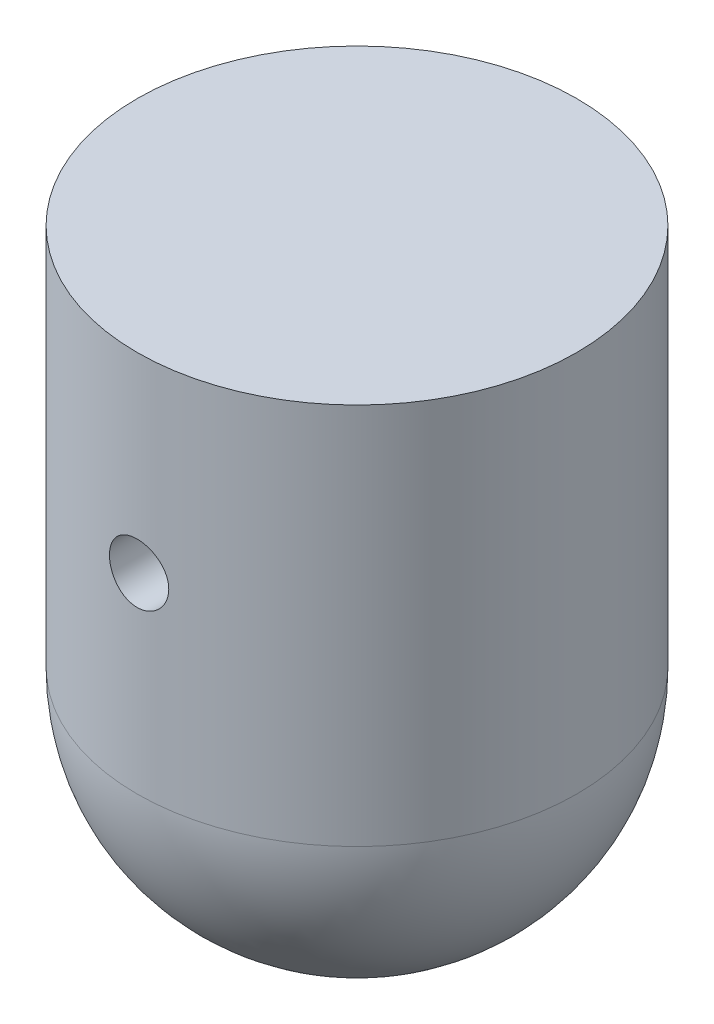
SolidWorks part; units mm, degrees
material "PLA"
ref_plane "Front Plane" through (0, 0, 0) normal (0, 0, 1) x (1, 0, 0)
ref_plane "Top Plane" through (0, 0, 0) normal (0, 1, 0) x (1, 0, 0)
ref_plane "Right Plane" through (0, 0, 0) normal (1, 0, 0) x (0, 0, -1)
sketch "Sketch1" plane through (0, 0, 0) normal (0, 1, 0) x (1, 0, 0)
  line L0 (0, -44.7868) -> (0, 44.7868) construction
  line L1 (0, 11.5) -> (0, -11.5)
  line L2 (0, 22.0214) -> (0, -22.0214) construction
  arc A0 (0, 11.5) -> (0, -11.5) centre (0, 0) ccw
  dimension "D1" = 11.5
revolve "Revolve1" add sketch "Sketch1" angle 180 about L2
sketch "Sketch4" plane through (0, 0, 0) normal (0, 1, 0) x (1, 0, 0)
  circle A0 centre (0, 0) radius 11.5
  dimension "D1" = 23
extrude "Boss-Extrude1" add sketch "Sketch4" along normal blind 20
sketch "Sketch5" plane through (0, 0, 0) normal (0, 0, 1) x (1, 0, 0)
  line L0 (0, -44.7868) -> (0, 44.7868) construction
  line L1 (11.5, 20) -> (-11.5, 20) construction
  circle A0 centre (0, 10) radius 1.55
  dimension "D1" = 3.1
  dimension "D2" = 10
extrude "Cut-Extrude1" cut sketch "Sketch5" against normal mid plane 23
equation "\"TubeDiam\"=11.5"
equation "\"D1@Sketch1\"=\"TubeDiam\""
equation "\"D1@Sketch4\"=\"TubeDiam\"*2"
equation "\"ExtrusionLength\"=20"
equation "\"D1@Boss-Extrude1\"=\"ExtrusionLength\""
equation "\"MountHoleSize\"=3.1"
equation "\"D1@Sketch5\"=\"MountHoleSize\""
equation "\"MountHoleDist\"=10"
equation "\"D2@Sketch5\"=\"MountHoleDist\""
equation "\"D1@Cut-Extrude1\"=\"TubeDiam\"*2"
